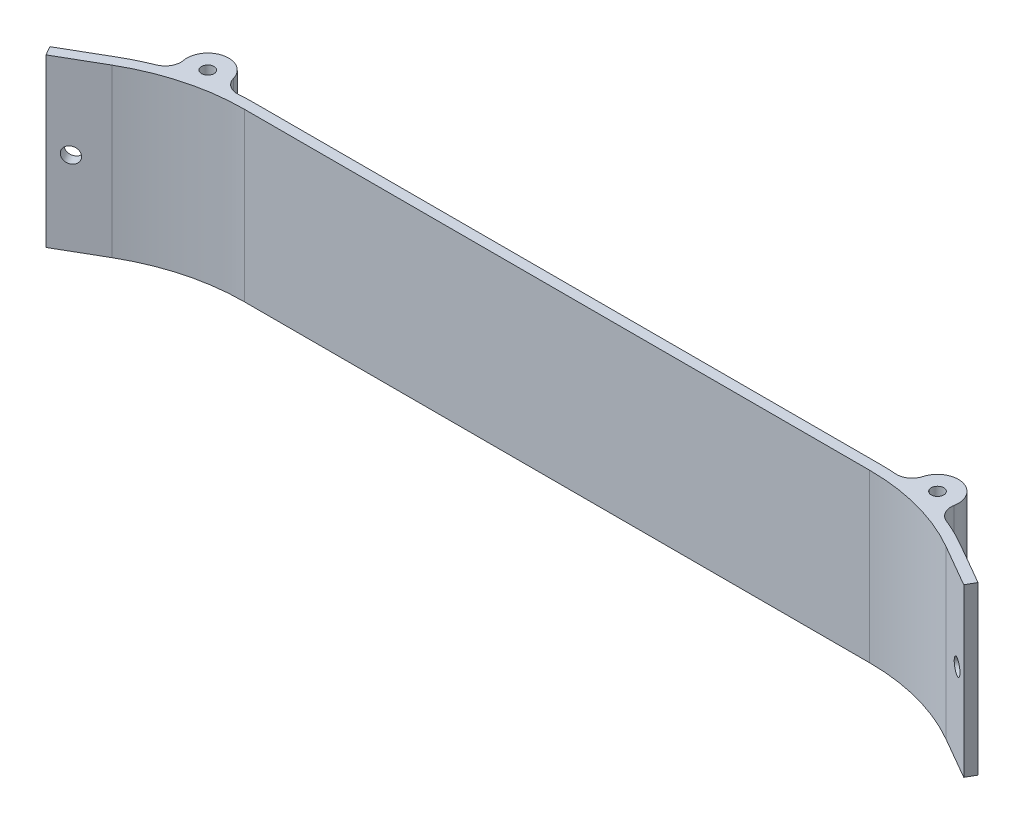
SolidWorks part; units mm, degrees
material "ABS"
ref_plane "Plan de face" through (0, 0, 0) normal (0, 0, 1) x (1, 0, 0)
ref_plane "Plan de dessus" through (0, 0, 0) normal (0, 1, 0) x (1, 0, 0)
ref_plane "Plan de droite" through (0, 0, 0) normal (1, 0, 0) x (0, 0, -1)
sketch "Esquisse1" plane through (0, 0, 0) normal (0, 1, 0) x (1, 0, 0)
  line L0 (0, 0) -> (-60, 0)
  line L1 (-80, -5.359) -> (-88.0385, -10)
  arc A1 (-60, 0) -> (-80, -5.359) centre (-60, -40) ccw
  point P0 (-70.718, 0)
  dimension "D1" = 70.718
  dimension "D3" = 40
  dimension "D2" = 30
  dimension "D4" = 20
  dimension "D5" = 60
extrude "Extru.-Mince1" add sketch "Esquisse1" along normal blind 32 thin
sketch "Esquisse2" plane through (0, 0, 0) normal (0, 1, 0) x (1, 0, 0)
  line L0 (0, 0) -> (-60, 0) construction
  circle A0 centre (-70, 3) radius 1.2
  circle A1 centre (-70, 3) radius 4
  dimension "D1" = 70
  dimension "D2" = 3
  dimension "D3" = 2.4
  dimension "D4" = 8
extrude "Boss.-Extru.1" add sketch "Esquisse2" along normal up to surface (32 mm away) up to face at (-57.35, 32, 2.5694)
fillet "Congé1" radius 3 2 edges at (-66.2808, 16, -1.5277) (-72.6879, 16, -0.0377)
sketch "Esquisse3" plane through (-17.6795, 0, -30.6218) normal (0.5, 0, 0.866) x (0.866, 0, -0.5)
  line L0 (-81.2436, 32) -> (-81.2436, 0) construction
  circle A0 centre (-77.7436, 16) radius 1.5
  point P4 (-81.2436, 16)
  dimension "D1" = 3
  dimension "D2" = 3.5
extrude "Enlèv. mat.-Extru.1" cut sketch "Esquisse3" against normal through all
mirror "Symétrie1" about plane through (0, 32, -2) normal (1, 0, 0) of bodies 103
